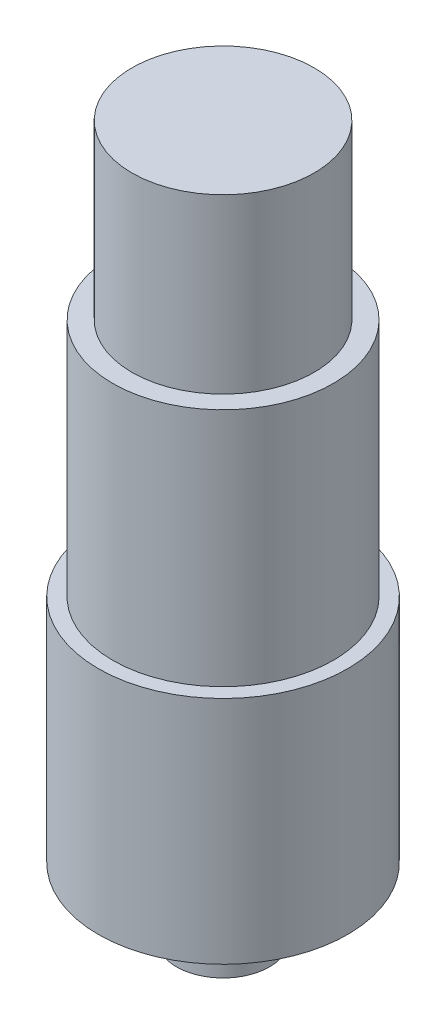
SolidWorks part; units mm, degrees
ref_plane "Спереди" through (0, 0, 0) normal (0, 0, 1) x (1, 0, 0)
ref_plane "Сверху" through (0, 0, 0) normal (0, 1, 0) x (1, 0, 0)
ref_plane "Справа" through (0, 0, 0) normal (1, 0, 0) x (0, 0, -1)
sketch "Эскиз1" plane through (0, 0, 0) normal (0, 0, 1) x (1, 0, 0)
  line L0 (0, 73.4471) -> (0, -43.7976) construction
  line L1 (0, 67) -> (9.5, 67)
  line L2 (9.5, 67) -> (9.5, 49)
  line L3 (9.5, 49) -> (11.5, 49)
  line L4 (11.5, 49) -> (11.5, 24)
  line L5 (11.5, 24) -> (13, 24)
  line L6 (13, 24) -> (13, 0)
  line L7 (13, 0) -> (0, 0)
  line L8 (9.5, 61) -> (0, 61)
  line L9 (4.85, 0) -> (4.85, -7)
  line L10 (4.85, -7) -> (0, -7)
  dimension "D1" = 67
  dimension "D2" = 26
  dimension "D3" = 23
  dimension "D4" = 19
  dimension "D5" = 6
  dimension "D6" = 12
  dimension "D7" = 37
  dimension "D8" = 9.7
  dimension "D9" = 7
revolve "Повернуть1" add sketch "Эскиз1" angle 360 about L0
